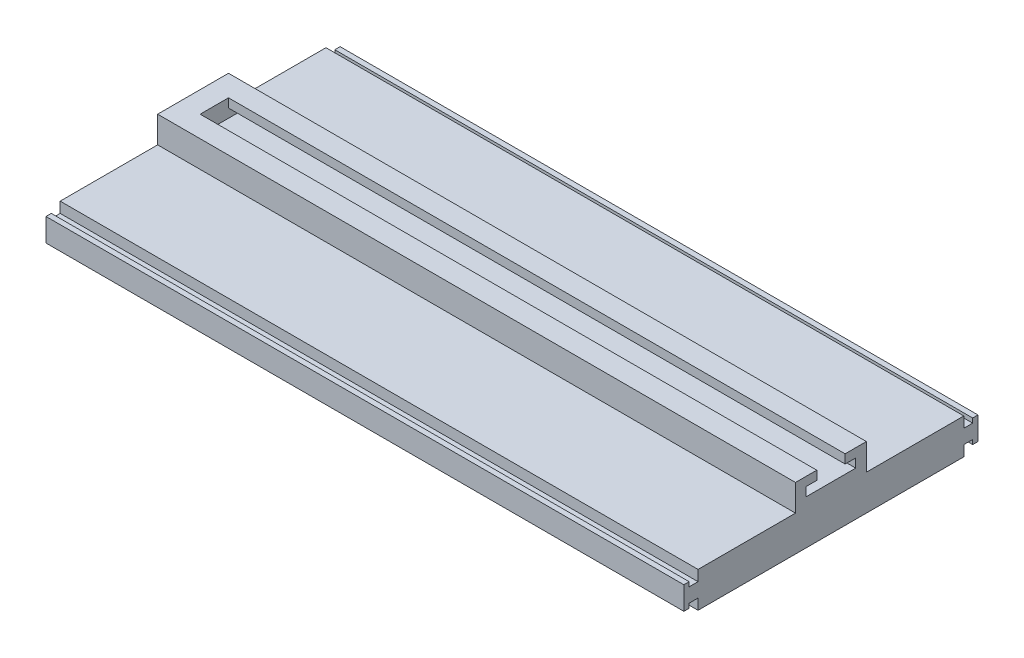
SolidWorks part; units mm, degrees
ref_plane "Front Plane" through (0, 0, 0) normal (0, 0, 1) x (1, 0, 0)
ref_plane "Top Plane" through (0, 0, 0) normal (0, 1, 0) x (1, 0, 0)
ref_plane "Right Plane" through (0, 0, 0) normal (1, 0, 0) x (0, 0, -1)
sketch "Sketch1" plane through (0, 0, 0) normal (0, 1, 0) x (1, 0, 0)
  line L1 (-228.6, -95.25) -> (228.6, -95.25)
  line L2 (-228.6, -95.25) -> (-228.6, 95.25)
  line L3 (-228.6, 95.25) -> (228.6, 95.25)
  line L4 (228.6, -95.25) -> (228.6, 95.25)
  line L5 (-228.6, -95.25) -> (228.6, 95.25) construction
  line L6 (-228.6, 95.25) -> (228.6, -95.25) construction
  point P0 (0, 0)
  dimension "D1" = 190.5
  dimension "D2" = 457.2
extrude "Boss-Extrude1" add sketch "Sketch1" along normal blind 25.4 contours L3 L4 L1 L2
sketch "Sketch2" plane through (0, 0, 95.25) normal (0, 0, 1) x (1, 0, 0)
  line L0 (228.6, 25.4) -> (228.6, 0) construction
  line L1 (228.6, 17.78) -> (-228.6, 17.78)
  line L2 (228.6, 17.78) -> (228.6, 7.62)
  line L3 (228.6, 7.62) -> (-228.6, 7.62)
  line L4 (-228.6, 17.78) -> (-228.6, 7.62)
  line L5 (-228.6, 25.4) -> (-228.6, 0) construction
  point P10 (228.6, 12.7)
  point P11 (228.6, 12.7)
  dimension "D1" = 10.16
extrude "Boss-Extrude2" add sketch "Sketch2" along normal blind 10.16
sketch "Sketch3" plane through (0, 17.78, 0) normal (0, 1, 0) x (1, 0, 0)
  line L1 (-228.6, -105.41) -> (228.6, -105.41)
  line L2 (-228.6, -105.41) -> (-228.6, -101.6)
  line L3 (-228.6, -101.6) -> (228.6, -101.6)
  line L4 (228.6, -105.41) -> (228.6, -101.6)
  line L5 (228.6, -105.41) -> (228.6, -95.25) construction
  dimension "D1" = 3.81
extrude "Boss-Extrude3" add sketch "Sketch3" along normal blind 3.175 and the other way blind 13.335
mirror "Mirror1" about plane through (0, 0, 0) normal (0, 0, 1) of "Boss-Extrude3", "Boss-Extrude1", "Boss-Extrude2"
sketch "Sketch5" plane through (0, 25.4, 0) normal (0, 1, 0) x (1, 0, 0)
  line L0 (-228.6, -95.25) -> (-228.6, 95.25) construction
  line L1 (-228.6, -25.4) -> (228.6, -25.4)
  line L2 (-228.6, -25.4) -> (-228.6, 25.4)
  line L3 (-228.6, 25.4) -> (228.6, 25.4)
  line L4 (228.6, -25.4) -> (228.6, 25.4)
  line L5 (228.6, -95.25) -> (228.6, 95.25) construction
  point P11 (-228.6, 0)
  point P12 (-228.6, 0)
  dimension "D1" = 50.8
extrude "Boss-Extrude4" add sketch "Sketch5" along normal blind 19.05
sketch "Sketch6" plane through (0, 44.45, 0) normal (0, 1, 0) x (1, 0, 0)
  line L0 (228.6, -25.4) -> (228.6, 25.4) construction
  line L1 (228.6, 10.16) -> (-213.36, 10.16)
  line L2 (228.6, 10.16) -> (228.6, -10.16)
  line L3 (228.6, -10.16) -> (-213.36, -10.16)
  line L4 (-213.36, 10.16) -> (-213.36, -10.16)
  line L5 (228.6, 25.4) -> (-228.6, 25.4) construction
  dimension "D1" = 15.24
  dimension "D2" = 15.24
  dimension "D3" = 15.24
extrude "Cut-Extrude1" cut sketch "Sketch6" against normal blind 12.7 contours L1 L4 L3 L2
sketch "Sketch7" plane through (0, 0, 10.16) normal (0, 0, -1) x (-1, 0, 0)
  line L0 (213.36, 31.75) -> (213.36, 44.45) construction
  line L1 (-228.6, 31.75) -> (213.36, 31.75)
  line L2 (-228.6, 31.75) -> (-228.6, 38.1)
  line L3 (-228.6, 38.1) -> (213.36, 38.1)
  line L4 (213.36, 31.75) -> (213.36, 38.1)
extrude "Cut-Extrude2" cut sketch "Sketch7" against normal blind 7.62 and the other way blind 27.94
sketch "Sketch8" plane through (0, 0, 0) normal (0, 0, 1) x (1, 0, 0)
  line L0 (44.0819, 0) -> (-32.1181, 0)
  line L1 (-32.1181, 0) -> (-25.4, -38.1)
  line L2 (-25.4, -38.1) -> (44.0819, 0)
  line L3 (-228.6, 0) -> (228.6, 0) construction
  line L4 (-228.6, 20.955) -> (-228.6, 4.445) construction
  dimension "D1" = 100
  dimension "D2" = 76.2
  dimension "D3" = 203.2
  dimension "D4" = 38.1
extrude "Boss-Extrude5" add sketch "Sketch8" along normal blind 25.4 and the other way blind 25.4
